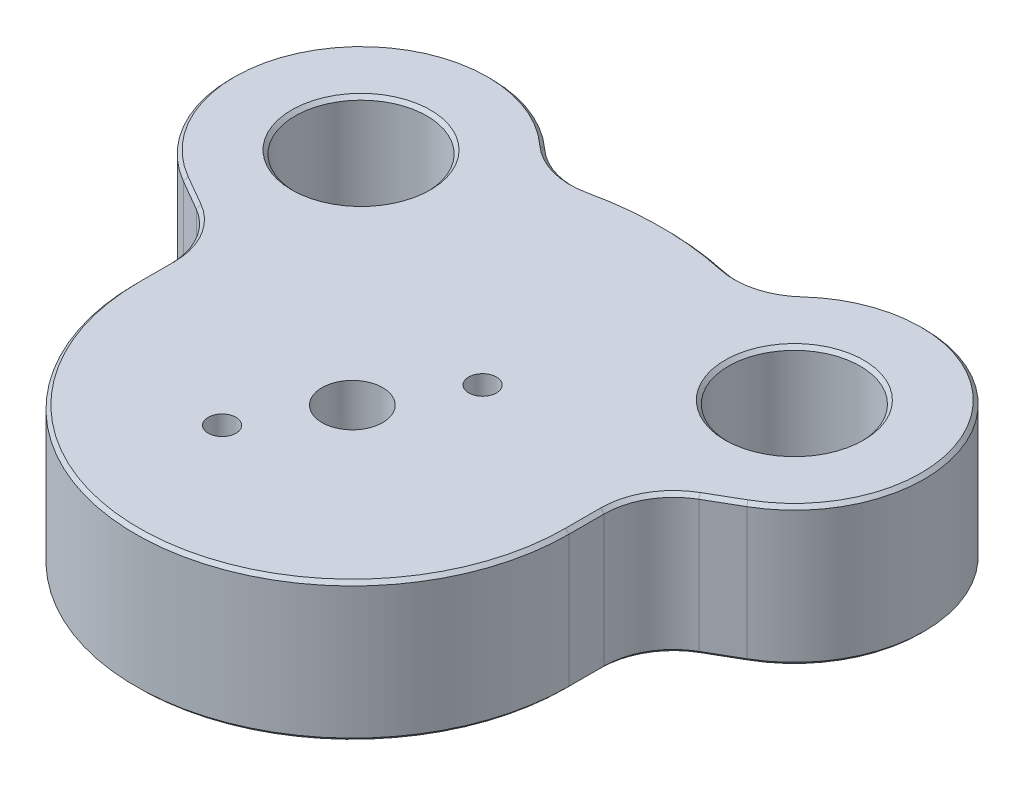
SolidWorks part; units mm, degrees
material "Plain Carbon Steel"
ref_plane "Front Plane" through (0, 0, 0) normal (0, 0, 1) x (1, 0, 0)
ref_plane "Top Plane" through (0, 0, 0) normal (0, 1, 0) x (1, 0, 0)
ref_plane "Right Plane" through (0, 0, 0) normal (1, 0, 0) x (0, 0, -1)
sketch "Sketch1" plane through (0, 0, 0) normal (0, 1, 0) x (1, 0, 0)
  line L0 (-100, 0) -> (100, 0) construction
  line L1 (0, -100) -> (0, 100) construction
  line L2 (-90, 0) -> (-90, 39.5049)
  line L3 (90, 0) -> (90, 39.5049)
  arc A0 (-90, 0) -> (90, 0) centre (0, 0) ccw
  arc A1 (-30.5618, 84.6521) -> (-90, 39.5049) centre (-62.5, 65) ccw
  arc A2 (90, 39.5049) -> (30.5618, 84.6521) centre (62.5, 65) ccw
  arc A3 (-30.5618, 84.6521) -> (-83.389, 33.8568) centre (0, 0) ccw construction
  arc A4 (-83.389, 33.8568) -> (-30.5618, 84.6521) centre (-62.5, 65) ccw construction
  arc A5 (30.5618, 84.6521) -> (-30.5618, 84.6521) centre (0, 0) ccw
  arc A6 (83.389, 33.8568) -> (30.5618, 84.6521) centre (0, 0) ccw construction
  arc A7 (30.5618, 84.6521) -> (83.389, 33.8568) centre (62.5, 65) ccw construction
  arc A8 (-83.389, 33.8568) -> (-90, 0) centre (0, 0) ccw construction
  arc A9 (90, 0) -> (83.389, 33.8568) centre (0, 0) ccw construction
  arc A10 (-90, 39.5049) -> (-83.389, 33.8568) centre (-62.5, 65) ccw construction
  arc A11 (83.389, 33.8568) -> (90, 39.5049) centre (62.5, 65) ccw construction
  dimension "D3" = 180
  dimension "D4" = 75
  dimension "D1" = 200
  dimension "D2" = 200
  dimension "D5" = 65
  dimension "D6" = 125
extrude "Boss-Extrude1" add sketch "Sketch1" along normal blind 40
sketch "Sketch2" plane through (0, 0, 0) normal (0, 1, 0) x (1, 0, 0)
  line L0 (-81.25, 32.524) -> (-62.5, 21.6987)
  line L1 (-90, 39.5049) -> (-90, 0) construction
  line L2 (-90, 39.5049) -> (-90, 0)
  line L3 (0, -62.5) -> (0, 62.5) construction
  line L4 (81.25, 32.524) -> (62.5, 21.6987)
  line L5 (90, 0) -> (90, 39.5049) construction
  line L6 (90, 0) -> (90, 39.5049)
  line L7 (-62.5, 0) -> (-62.5, 21.6987)
  line L8 (62.5, 0) -> (62.5, 21.6987)
  arc A0 (-62.5, 0) -> (62.5, 0) centre (0, 0) ccw
  arc A1 (-30.5618, 84.6521) -> (-90, 39.5049) centre (-62.5, 65) ccw construction
  arc A2 (-90, 39.5049) -> (-81.25, 32.524) centre (-62.5, 65) ccw
  arc A3 (-81.25, 32.524) -> (-69.2916, 28.1201) centre (-62.5, 65) ccw construction
  arc A4 (-30.5618, 84.6521) -> (-90, 39.5049) centre (-62.5, 65) ccw construction
  arc A5 (-90, 0) -> (90, 0) centre (0, 0) ccw construction
  arc A6 (-90, 0) -> (90, 0) centre (0, 0) ccw
  arc A7 (90, 39.5049) -> (81.25, 32.524) centre (62.5, 65) cw
  arc A8 (0, 62.5) -> (-59.2695, 19.8336) centre (0, 0) ccw construction
  arc A9 (59.2695, 19.8336) -> (0, 62.5) centre (0, 0) ccw construction
  dimension "D1" = 125
  dimension "D2" = 60
extrude "Cut-Extrude4" cut sketch "Sketch2" along normal through all
fillet "Fillet1" radius 20 4 edges at (30.5618, 20, -84.6521) (-30.5618, 20, -84.6521) (62.5, 20, -21.6987) (-62.5, 20, -21.6987)
sketch "Sketch3" plane through (0, 0, 0) normal (0, 1, 0) x (1, 0, 0)
  circle A0 centre (-62.5, 65) radius 19
  circle A1 centre (62.5, 65) radius 19
  dimension "D1" = 38
extrude "Cut-Extrude2" cut sketch "Sketch3" along normal up to next
hole_wizard "M20 Tapped Hole1" positions "Sketch7" profile "Sketch5" tap size "M20" standard "ISO" end condition through all
sketch "Sketch7" plane through (0, 40, 0) normal (0, 1, 0) x (1, 0, 0)
  point P0 (0, 0)
sketch "Sketch5" plane through (0, 40, 0) normal (1, 0, 0) x (0, 0, 1)
  line L0 (0, 0) -> (0, 40)
  line L1 (0, 40) -> (8.75, 40)
  line L2 (8.75, 40) -> (8.75, 0)
  line L5 (8.75, 0) -> (0, 0)
  line L11 (0, -6.35) -> (0, 107.95) construction
  dimension "Thru Tap Drill Dia." = 17.5
  dimension "Thru Tap Drill Depth" = 40
cosmetic thread "Hole Thread1" parameters "D2"=20
sketch "Sketch8" plane through (0, 0, 0) normal (0, -1, 0) x (1, 0, 0)
  circle A0 centre (0, 0) radius 15
  dimension "D1" = 30
extrude "Cut-Extrude3" cut sketch "Sketch8" against normal blind 10
hole_wizard "M6 Tapped Hole1" positions "Sketch11" profile "Sketch10" tap size "M6" standard "ISO"
sketch "Sketch11" plane through (0, 0, 0) normal (0, -1, 0) x (-1, 0, 0)
  point P0 (-21.6506, -12.2377)
  point P3 (21.6506, -12.5)
  point P7 (0, 25)
sketch "Sketch10" plane through (21.6506, 0, 12.2377) normal (1, 0, 0) x (0, 0, -1)
  line L0 (0, 0) -> (0, 18.5022)
  line L1 (0, 18.5022) -> (2.5, 17)
  line L2 (2.5, 17) -> (2.5, 0)
  line L5 (2.5, 0) -> (0, 0)
  line L10 (0, 18.5022) -> (-2.5, 17) construction
  line L11 (0, -6.35) -> (0, 107.95) construction
  dimension "Tap Drill Dia." = 5
  dimension "Tap Drill Depth" = 17
  dimension "Drill Angle" = 118
cosmetic thread "Hole Thread2" parameters "D1"=12, "D2"=6
cosmetic thread "Hole Thread3" parameters "D1"=12, "D2"=6
cosmetic thread "Hole Thread4" parameters "D1"=12, "D2"=6
hole_wizard "Ø8.0mm Dowel Hole1" positions "Sketch14" profile "Sketch13" hole size "Ø8.0" standard "ISO" end condition through all
sketch "Sketch14" plane through (0, 0, 0) normal (0, -1, 0) x (-1, 0, 0)
  point P0 (13.75, -23.8157)
  point P3 (-13.75, 23.8157)
sketch "Sketch13" plane through (-13.75, 0, 23.8157) normal (1, 0, 0) x (0, 0, -1)
  line L0 (0, 0) -> (0, 40)
  line L1 (0, 40) -> (4, 40)
  line L2 (4, 40) -> (4, 0)
  line L5 (4, 0) -> (0, 0)
  line L11 (0, -6.35) -> (0, 107.95) construction
  dimension "Thru Hole Dia." = 8
  dimension "Thru Hole Depth" = 40
chamfer "Chamfer1" distance 1 angle 45 28 edges at (-62.5, 0, -46) (62.5, 0, -46) (62.5, 40, -46) (-62.5, 40, -46) (0, 0, -90) (28.8639, 0, -88.103) (-28.8639, 0, -88.103) (92.7493, 0, -87.1637) (-92.7493, 0, -87.1637) (76.875, 0, -29.9981) (-76.875, 0, -29.9981) (65.1795, 0, -20.1517) (-65.1795, 0, -20.1517) (62.5, 0, -5.0759) (-62.5, 0, -5.0759) (0, 0, 62.5) (0, 40, -90) (28.8639, 40, -88.103) (-28.8639, 40, -88.103) (92.7493, 40, -87.1637) (-92.7493, 40, -87.1637) (76.875, 40, -29.9981) (-76.875, 40, -29.9981) (65.1795, 40, -20.1517) (-65.1795, 40, -20.1517) (62.5, 40, -5.0759) (-62.5, 40, -5.0759) (0, 40, 62.5)
